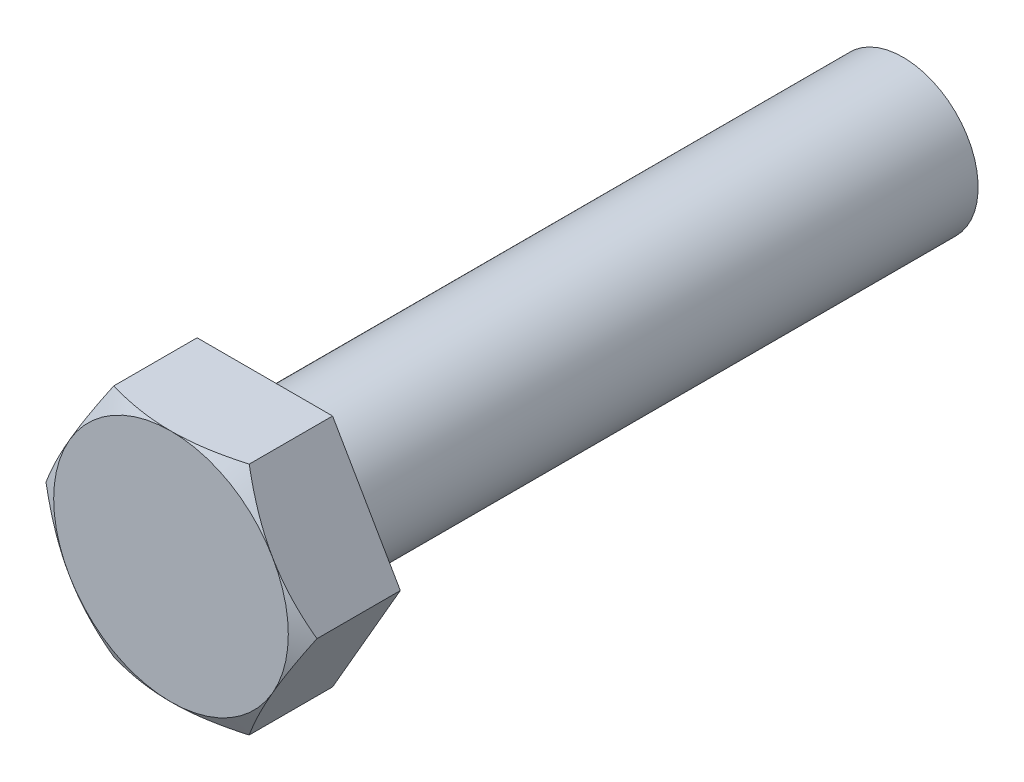
SolidWorks part; units mm, degrees
ref_plane "Ön Düzlem" through (0, 0, 0) normal (0, 0, 1) x (1, 0, 0)
ref_plane "Üst Düzlem" through (0, 0, 0) normal (0, 1, 0) x (1, 0, 0)
ref_plane "Sağ Düzlem" through (0, 0, 0) normal (1, 0, 0) x (0, 0, -1)
sketch "Çizim1" plane through (0, 0, 0) normal (0, 0, 1) x (1, 0, 0)
  line L1 (14.4338, 0) -> (7.2169, 12.5)
  line L2 (7.2169, 12.5) -> (-7.2169, 12.5)
  line L3 (-7.2169, 12.5) -> (-14.4338, 0)
  line L4 (-14.4338, 0) -> (-7.2169, -12.5)
  line L5 (-7.2169, -12.5) -> (7.2169, -12.5)
  line L6 (7.2169, -12.5) -> (14.4338, 0)
  circle A0 centre (0, 0) radius 12.5 construction
  dimension "D1" = 25
extrude "Yükseklik-Ekstrüzyon1" add sketch "Çizim1" along normal blind 10
sketch "Çizim2" plane through (0, 0, 0) normal (0, 0, -1) x (-1, 0, 0)
  circle A0 centre (0, 0) radius 8
  dimension "D1" = 16
extrude "Yükseklik-Ekstrüzyon2" add sketch "Çizim2" along normal blind 68
sketch "Çizim3" plane through (0, 0, 10) normal (0, 0, 1) x (1, 0, 0)
  circle A0 centre (0, 0) radius 12.5
extrude "Kes-Ekstrüzyon2" cut sketch "Çizim3" against normal blind 10 draft 60 flip side to cut
